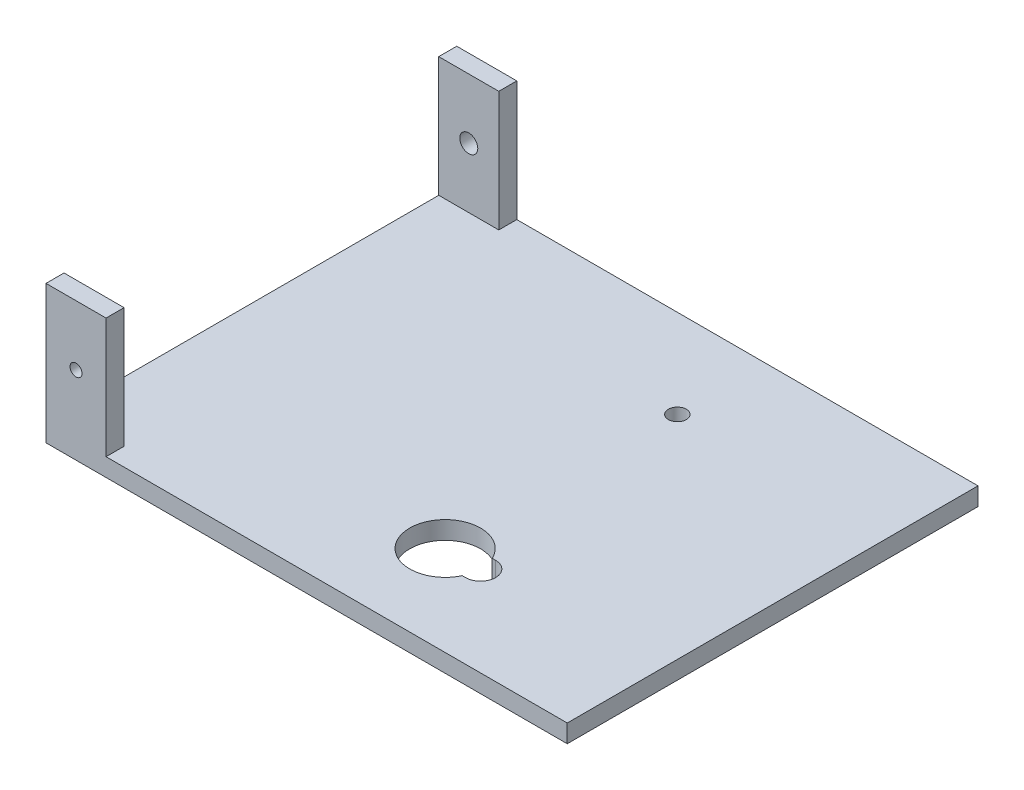
SolidWorks part; units mm, degrees
ref_plane "Front Plane" through (0, 0, 0) normal (0, 0, 1) x (1, 0, 0)
ref_plane "Top Plane" through (0, 0, 0) normal (0, 1, 0) x (1, 0, 0)
ref_plane "Right Plane" through (0, 0, 0) normal (1, 0, 0) x (0, 0, -1)
sketch "Sketch1" plane through (0, 0, 0) normal (0, 1, 0) x (1, 0, 0)
  line L1 (0, 0) -> (86.8, 0)
  line L2 (0, 0) -> (0, -68.4)
  line L3 (0, -68.4) -> (86.8, -68.4)
  line L4 (86.8, 0) -> (86.8, -68.4)
  dimension "D1" = 68.4
  dimension "D2" = 86.8
extrude "Boss-Extrude1" add sketch "Sketch1" along normal blind 3
sketch "Sketch2" plane through (0, 3, 0) normal (0, 1, 0) x (1, 0, 0)
  line L1 (0, -68.4) -> (10, -68.4)
  line L2 (0, -68.4) -> (0, -65.4)
  line L3 (0, -65.4) -> (10, -65.4)
  line L4 (10, -68.4) -> (10, -65.4)
  dimension "D1" = 10
  dimension "D2" = 3
extrude "Boss-Extrude2" add sketch "Sketch2" along normal blind 20
sketch "Sketch3" plane through (0, 3, 0) normal (0, 1, 0) x (1, 0, 0)
  line L1 (0, 0) -> (10, 0)
  line L2 (0, 0) -> (0, -3)
  line L3 (0, -3) -> (10, -3)
  line L4 (10, 0) -> (10, -3)
  dimension "D1" = 10
  dimension "D2" = 3
extrude "Boss-Extrude3" add sketch "Sketch3" along normal blind 20
sketch "Sketch4" plane through (0, 0, 68.4) normal (0, 0, 1) x (1, 0, 0)
  line L0 (0, 23) -> (10, 23) construction
  circle A0 centre (5, 13) radius 1
  point P5 (5, 23)
  dimension "D1" = 2
  dimension "D2" = 10
extrude "Cut-Extrude1" cut sketch "Sketch4" against normal blind 20
sketch "Sketch5" plane through (0, 0, 3) normal (0, 0, 1) x (1, 0, 0)
  line L0 (0, 23) -> (10, 23) construction
  circle A0 centre (5, 13) radius 1.5
  point P5 (5, 23)
  dimension "D1" = 3
  dimension "D2" = 10
extrude "Cut-Extrude2" cut sketch "Sketch5" against normal blind 20
sketch "Sketch8" plane through (0, 0, 0) normal (0, -1, 0) x (1, 0, 0)
  circle A0 centre (51.4652, 53.4) radius 1.5
  circle A1 centre (51.4652, 14.7308) radius 1.5
  point P6 (51.4652, 51.9)
  point P7 (51.4652, 30)
  dimension "D1" = 3
  dimension "D2" = 3
extrude "Cut-Extrude3" cut sketch "Sketch8" against normal blind 20
sketch "Sketch9" plane through (0, 0, 0) normal (0, -1, 0) x (1, 0, 0)
  line L0 (56.8093, 55.9) -> (57.3693, 55.9)
  line L2 (57.3693, 50.9) -> (56.8093, 50.9)
  arc A0 (56.8093, 55.9) -> (56.8093, 50.9) centre (51.4652, 53.4) ccw
  circle A2 centre (51.4652, 53.4) radius 1.5 construction
  arc A3 (57.3693, 55.9) -> (57.3693, 50.9) centre (57.3693, 53.4) cw
  dimension "D1" = 11.8
  dimension "D3" = 2.5
  dimension "D2" = 0.56
extrude "Cut-Extrude4" cut sketch "Sketch9" against normal blind 10
